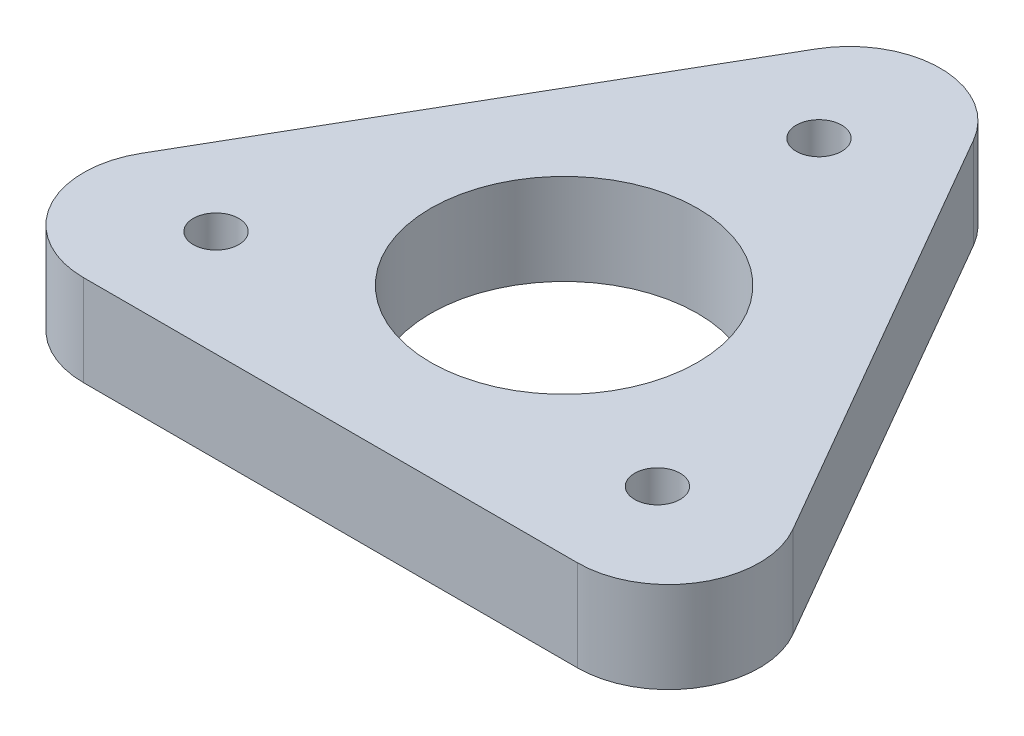
SolidWorks part; units mm, degrees
ref_plane "Plan de face" through (0, 0, 0) normal (0, 0, 1) x (1, 0, 0)
ref_plane "Plan de dessus" through (0, 0, 0) normal (0, 1, 0) x (1, 0, 0)
ref_plane "Plan de droite" through (0, 0, 0) normal (1, 0, 0) x (0, 0, -1)
sketch "Esquisse1" plane through (0, 0, 0) normal (0, 1, 0) x (1, 0, 0)
  line L0 (0, 0) -> (0, 15.4) construction
  line L1 (-2.5981, 10.9) -> (-10.7387, -3.2)
  line L2 (-8.1406, -7.7) -> (8.1406, -7.7)
  line L3 (10.7387, -3.2) -> (2.5981, 10.9)
  circle A0 centre (0, 0) radius 7.7 construction
  circle A1 centre (0, 0) radius 4.4
  circle A2 centre (0, 8.4) radius 0.75
  circle A3 centre (7.2746, -4.2) radius 0.75
  circle A4 centre (-7.2746, -4.2) radius 0.75
  arc A5 (8.1406, -7.7) -> (10.7387, -3.2) centre (8.1406, -4.7) ccw
  arc A6 (-10.7387, -3.2) -> (-8.1406, -7.7) centre (-8.1406, -4.7) ccw
  arc A7 (-2.5981, 10.9) -> (2.5981, 10.9) centre (0, 9.4) cw
  point P9 (7.0005, -5.9267)
  point P10 (0, 0)
  point P15 (0, 0)
  dimension "D1" = 7.7
  dimension "D2" = 1.5
  dimension "D3" = 8.8
  dimension "D6" = 3
  dimension "D4" = 8.4
  dimension "D5" = 3
extrude "Boss.-Extru.1" add sketch "Esquisse1" along normal blind 3
